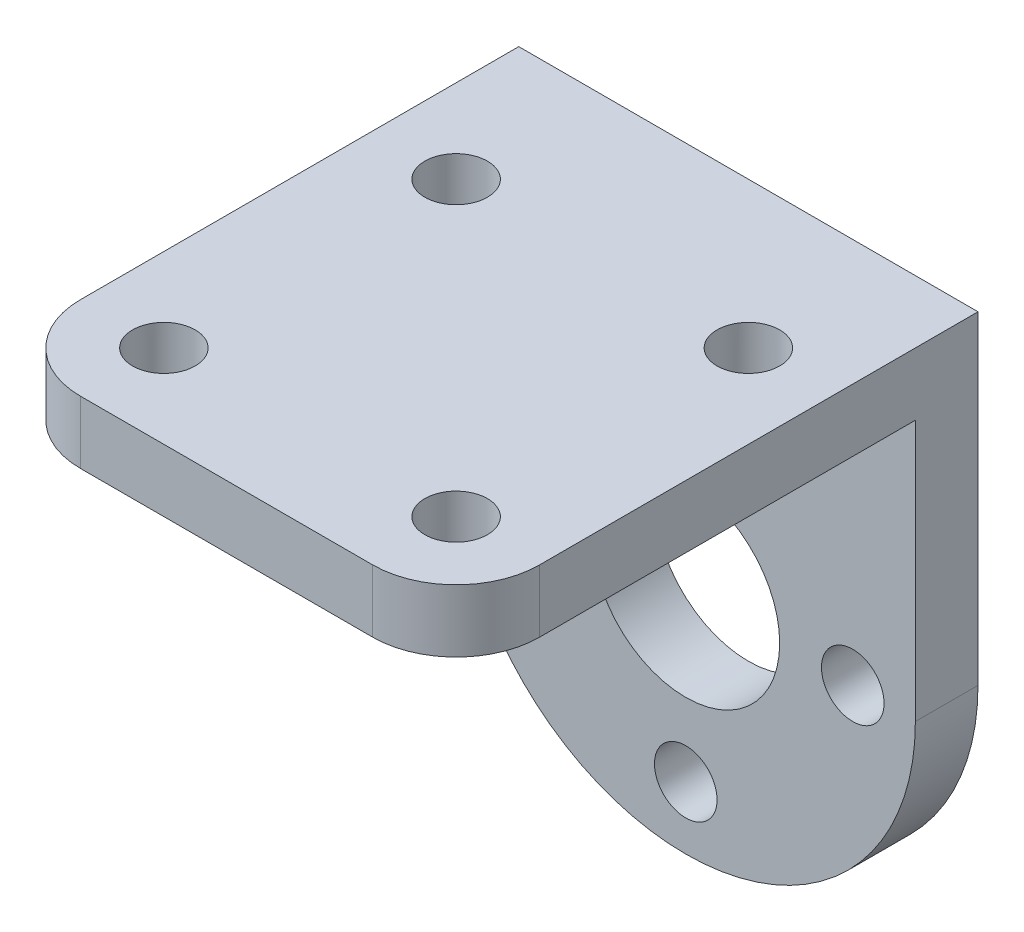
SolidWorks part; units mm, degrees
ref_plane "Plan de face" through (0, 0, 0) normal (0, 0, 1) x (1, 0, 0)
ref_plane "Plan de dessus" through (0, 0, 0) normal (0, 1, 0) x (1, 0, 0)
ref_plane "Plan de droite" through (0, 0, 0) normal (1, 0, 0) x (0, 0, -1)
sketch "Esquisse1" plane through (0, 0, 0) normal (0, 0, 1) x (1, 0, 0)
  line L2 (11, 0) -> (11, 15.5)
  line L3 (11, 15.5) -> (-11, 15.5)
  line L4 (-11, 0) -> (-11, 15.5)
  arc A0 (-11, 0) -> (11, 0) centre (0, 0) ccw
  circle A1 centre (8, 0) radius 1.5
  circle A2 centre (0, -8) radius 1.5
  circle A3 centre (0, 8) radius 1.5
  circle A4 centre (-8, 0) radius 1.5
  circle A6 centre (0, 0) radius 4.5
  dimension "D2" = 3
  dimension "D3" = 3
  dimension "D4" = 3
  dimension "D5" = 3
  dimension "D6" = 9
  dimension "D1" = 7.5
extrude "Boss.-Extru.1" add sketch "Esquisse1" along normal blind 3
sketch "Esquisse2" plane through (0, 0, 3) normal (0, 0, 1) x (1, 0, 0)
  line L0 (-11, 15.5) -> (-11, 0) construction
  line L1 (11, 15.5) -> (-11, 15.5)
  line L2 (11, 15.5) -> (11, 12.5)
  line L3 (11, 12.5) -> (-11, 12.5)
  line L4 (-11, 15.5) -> (-11, 12.5)
  dimension "D1" = 3
extrude "Boss.-Extru.2" add sketch "Esquisse2" along normal blind 22
sketch "Esquisse3" plane through (0, 12.5, 0) normal (0, -1, 0) x (1, 0, 0)
  line L0 (-11, 25) -> (11, 25) construction
  line L2 (11, 25) -> (11, 3) construction
  line L3 (0, 25) -> (0, 3) construction
  line L4 (11, 3) -> (-11, 3) construction
  line L5 (-11, 14) -> (11, 14) construction
  line L6 (-11, 25) -> (-11, 3) construction
  circle A0 centre (7, 21) radius 1.5
  circle A1 centre (-7, 21) radius 1.5
  circle A2 centre (7, 7) radius 1.5
  circle A3 centre (-7, 7) radius 1.5
  dimension "D1" = 3
  dimension "D2" = 4
  dimension "D3" = 4
extrude "Enlèv. mat.-Extru.1" cut sketch "Esquisse3" against normal up to next
fillet "Congé1" radius 4 2 edges at (11, 14, 25) (-11, 14, 25)
